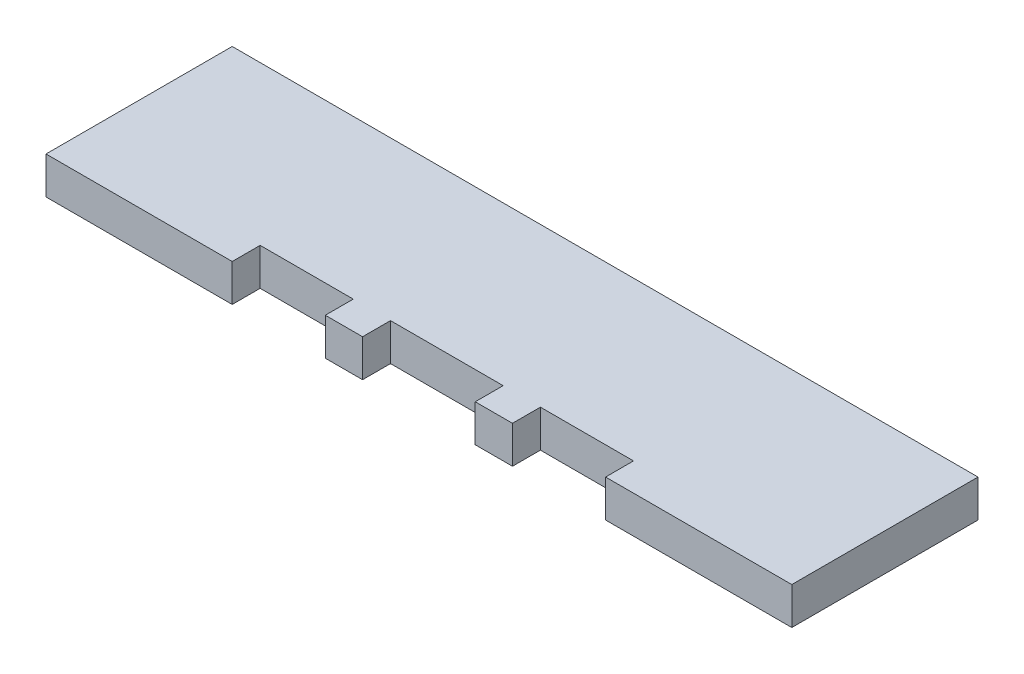
SolidWorks part; units mm, degrees
ref_plane "Спереди" through (0, 0, 0) normal (0, 0, 1) x (1, 0, 0)
ref_plane "Сверху" through (0, 0, 0) normal (0, 1, 0) x (1, 0, 0)
ref_plane "Справа" through (0, 0, 0) normal (1, 0, 0) x (0, 0, -1)
other "Configuration Table"
sketch "Эскиз1" plane through (0, 0, 0) normal (0, 1, 0) x (1, 0, 0)
  line L0 (0, 0) -> (0, 3)
  line L1 (0, 3) -> (40.1, 3)
  line L2 (40.1, 3) -> (40.1, 0)
  line L3 (40.1, 0) -> (60.1, 0)
  line L4 (60.1, 0) -> (60.1, 20)
  line L5 (60.1, 20) -> (-20, 20)
  line L6 (-20, 20) -> (-20, 0)
  line L7 (-20, 0) -> (0, 0)
  dimension "D1" = 40.1
  dimension "D2" = 20
  dimension "D3" = 20
  dimension "D4" = 3
  dimension "D5" = 20
extrude "Бобышка-Вытянуть1" add sketch "Эскиз1" along normal blind 4
sketch "Эскиз2" plane through (0, 0, -3) normal (0, 0, 1) x (1, 0, 0)
  line L0 (0, 4) -> (40.1, 4) construction
  line L1 (26.1, 4) -> (30.1, 4)
  line L2 (26.1, 4) -> (26.1, 0)
  line L3 (26.1, 0) -> (30.1, 0)
  line L4 (30.1, 4) -> (30.1, 0)
  line L5 (0, 0) -> (40.1, 0) construction
  line L6 (40.1, 4) -> (40.1, 0) construction
  line L7 (10, 4) -> (10, 0)
  line L8 (10, 4) -> (14, 4)
  line L9 (14, 4) -> (14, 0)
  line L10 (10, 0) -> (14, 0)
  line L11 (0, 4) -> (0, 0) construction
  dimension "D1" = 4
  dimension "D2" = 10
  dimension "D4" = 10
  dimension "D3" = 2
extrude "Бобышка-Вытянуть2" add sketch "Эскиз2" along normal blind 3
